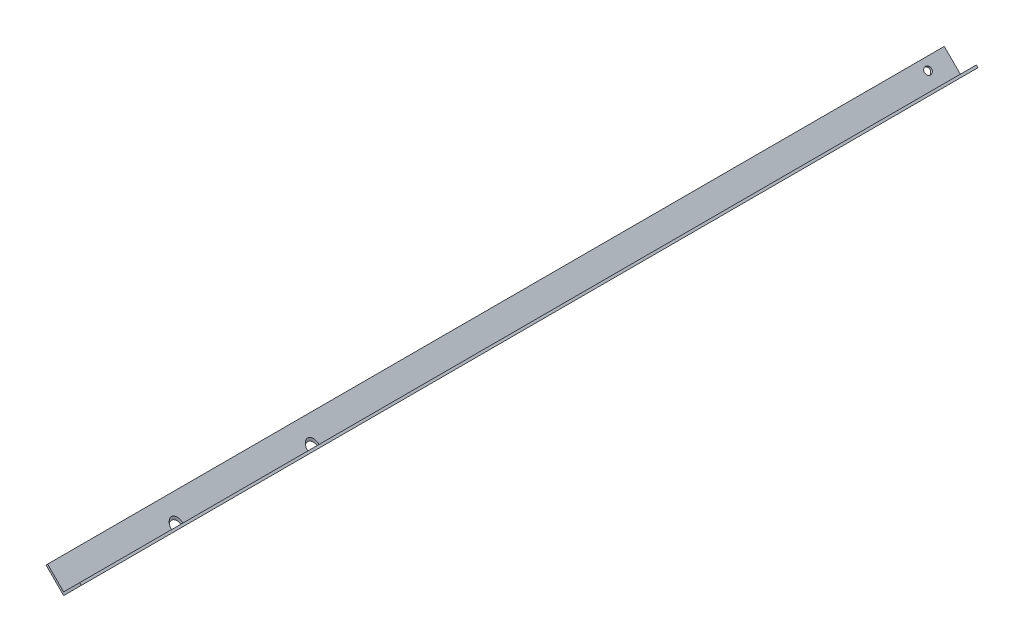
SolidWorks part; units mm, degrees
material "6061 Alloy"
ref_plane "Front Plane" through (0, 0, 0) normal (0, 0, 1) x (1, 0, 0)
ref_plane "Top Plane" through (0, 0, 0) normal (0, 1, 0) x (1, 0, 0)
ref_plane "Right Plane" through (0, 0, 0) normal (1, 0, 0) x (0, 0, -1)
sketch "Sketch1" plane through (0, 0, 0) normal (0, 0, 1) x (1, 0, 0)
  line L0 (0, 0) -> (-8.9803, 8.9803)
  line L1 (-8.9803, 8.9803) -> (-9.8783, 8.0822)
  line L2 (-9.8783, 8.0822) -> (0, -1.7961)
  line L3 (0, -1.7961) -> (9.8783, 8.0822)
  line L4 (9.8783, 8.0822) -> (8.9803, 8.9803)
  line L5 (8.9803, 8.9803) -> (0, 0)
  line L6 (-13.872, 0) -> (16.6117, 0) construction
  dimension "D1" = 1.27
  dimension "D2" = 12.7
extrude "Boss-Extrude1" add sketch "Sketch1" along normal blind 501.65
sketch "Sketch2" plane through (0, 0, 0) normal (-0.7071, 0.7071, 0) x (0, 0, 1)
  line L0 (501.65, 12.7) -> (0, 12.7) construction
  line L1 (0, 12.7) -> (0, 0) construction
  circle A0 centre (6.35, 7.62) radius 1.9844
  circle A1 centre (19.05, 7.62) radius 1.9844
  dimension "D4" = 3.9688
  dimension "D1" = 5.08
  dimension "D2" = 5.08
  dimension "D3" = 6.35
  dimension "D5" = 19.05
sketch "Sketch3" plane through (0, 0, 0) normal (0.7071, 0.7071, 0) x (0, 0, -1)
  line L0 (0, 0) -> (0, 12.7) construction
  line L1 (-501.65, 12.7) -> (0, 12.7) construction
  circle A0 centre (-12.7, 7.62) radius 1.9844
  dimension "D3" = 3.9688
  dimension "D1" = 12.7
  dimension "D2" = 5.08
extrude "Cut-Extrude1" cut sketch "Sketch2" against normal through all
extrude "Cut-Extrude2" cut sketch "Sketch3" against normal through all
sketch "Sketch4" plane through (0, 0, 0) normal (0, 1, 0) x (1, 0, 0)
  line L0 (0, -5.927) -> (0, 5.927) construction
  line L1 (8.9803, -501.65) -> (0, -501.65) construction
  circle A0 centre (0, -438.15) radius 3.175
  circle A1 centre (0, -361.95) radius 3.175
  dimension "D1" = 6.35
  dimension "D2" = 6.35
  dimension "D3" = 76.2
  dimension "D4" = 63.5
extrude "Cut-Extrude4" cut sketch "Sketch4" against normal through all both and the other way through all
